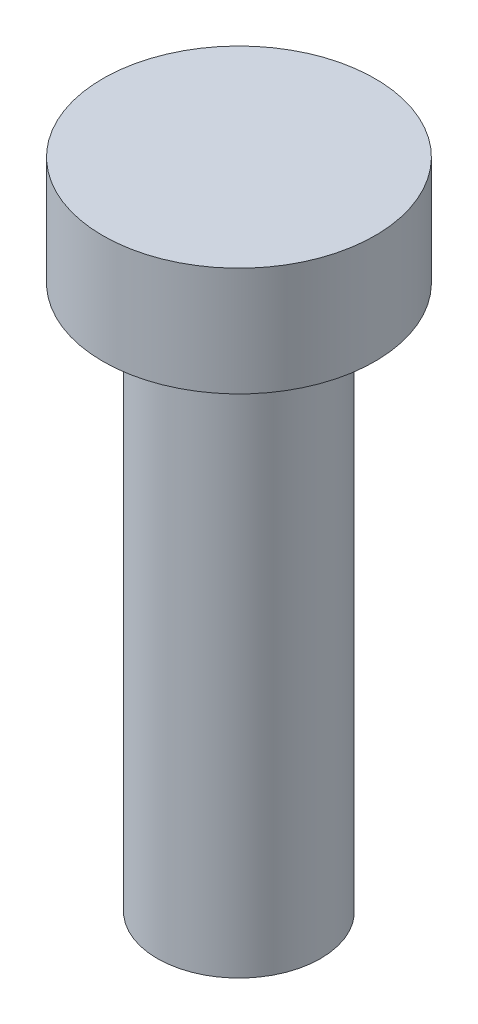
SolidWorks part; units mm, degrees
ref_plane "Plan de face" through (0, 0, 0) normal (0, 0, 1) x (1, 0, 0)
ref_plane "Plan de dessus" through (0, 0, 0) normal (0, 1, 0) x (1, 0, 0)
ref_plane "Plan de droite" through (0, 0, 0) normal (1, 0, 0) x (0, 0, -1)
sketch "Esquisse1" plane through (0, 0, 0) normal (0, 1, 0) x (1, 0, 0)
  circle A0 centre (0, 0) radius 1.5
  dimension "D1" = 3
extrude "Extrusion1" add sketch "Esquisse1" along normal blind 10
sketch "Esquisse2" plane through (0, 10, 0) normal (0, 1, 0) x (1, 0, 0)
  circle A0 centre (0, 0) radius 2.5
  dimension "D1" = 5
extrude "Extrusion2" add sketch "Esquisse2" along normal blind 2
